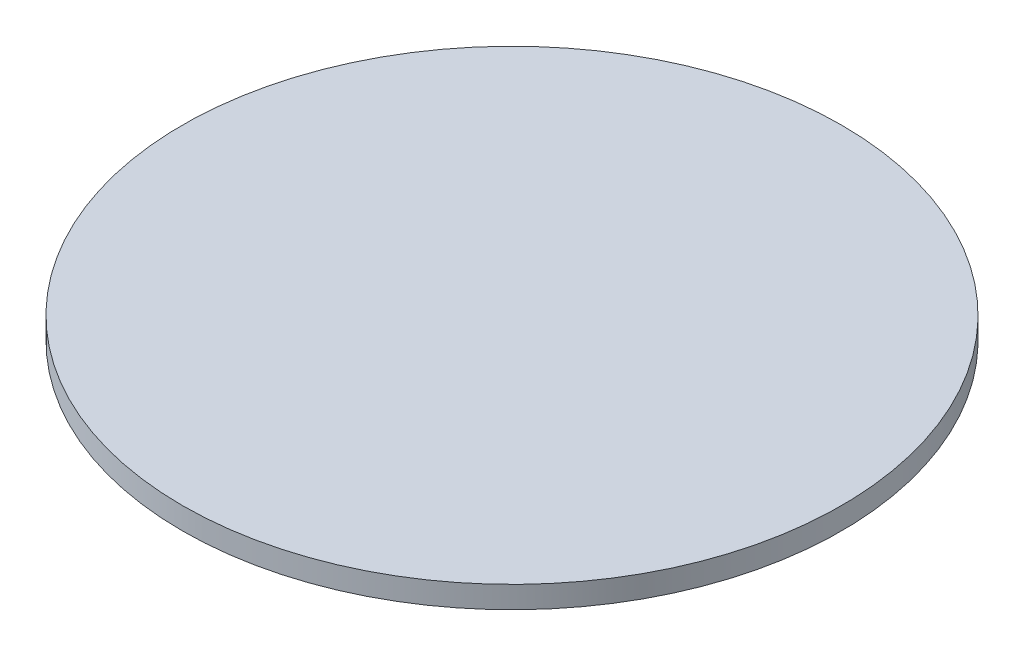
SolidWorks part; units mm, degrees
ref_plane "Ebene vorne" through (0, 0, 0) normal (0, 0, 1) x (1, 0, 0)
ref_plane "Ebene oben" through (0, 0, 0) normal (0, 1, 0) x (1, 0, 0)
ref_plane "Ebene rechts" through (0, 0, 0) normal (1, 0, 0) x (0, 0, -1)
sketch "Skizze1" plane through (0, 0, 0) normal (0, 1, 0) x (1, 0, 0)
  circle A0 centre (0, 0) radius 10
  dimension "D1" = 20
extrude "Aufsatz-Linear austragen1" add sketch "Skizze1" against normal blind 1
sketch "Skizze2" plane through (0, 0, 0) normal (0, 1, 0) x (1, 0, 0)
  circle A0 centre (0, 0) radius 30
  dimension "D1" = 60
extrude "Aufsatz-Linear austragen2" add sketch "Skizze2" along normal blind 2
sketch "Skizze3" plane through (0, -1, 0) normal (0, -1, 0) x (1, 0, 0)
  line L0 (-7.0711, 7.0711) -> (-9.1924, 9.1924)
  line L1 (7.0711, 7.0711) -> (9.1924, 9.1924)
  line L2 (7.0711, -7.0711) -> (9.1924, -9.1924)
  line L3 (-7.0711, -7.0711) -> (-9.1924, -9.1924)
  arc A0 (9.1924, 9.1924) -> (9.1924, -9.1924) centre (0, 0) cw
  arc A1 (-9.1924, 9.1924) -> (-9.1924, -9.1924) centre (0, 0) ccw
  circle A2 centre (0, 0) radius 10 construction
  circle A3 centre (0, 0) radius 10 construction
  arc A4 (-7.0711, 7.0711) -> (-7.0711, -7.0711) centre (0, 0) ccw
  arc A5 (7.0711, 7.0711) -> (7.0711, -7.0711) centre (0, 0) cw
extrude "Aufsatz-Linear austragen3" add sketch "Skizze3" along normal blind 1 separate body
sketch "Skizze4" plane through (0, -1, 0) normal (0, -1, 0) x (1, 0, 0)
  circle A0 centre (0, 0) radius 10
extrude "Aufsatz-Linear austragen4" add sketch "Skizze4" along normal blind 1
sketch "Skizze8" plane through (0, -1, 0) normal (0, 1, 0) x (1, 0, 0)
  line L0 (9.1924, -9.1924) -> (7.0711, -7.0711) construction
  line L1 (10.0765, -8.2136) -> (7.7376, -6.3348)
  line L2 (9.1924, -9.1924) -> (7.0711, -7.0711)
  line L3 (-7.0711, 7.0711) -> (-9.1924, 9.1924)
  line L4 (-10.0575, 8.2369) -> (-7.7328, 6.3407)
  arc A0 (7.0711, -7.0711) -> (7.7376, -6.3348) centre (0, 0) ccw
  arc A1 (9.1924, -9.1924) -> (10.0765, -8.2136) centre (0, 0) ccw
  arc A2 (-7.0711, 7.0711) -> (-7.7328, 6.3407) centre (0, 0) ccw
  arc A3 (-9.1924, 9.1924) -> (-10.0575, 8.2369) centre (0, 0) ccw
extrude "Aufsatz-Linear austragen15" add sketch "Skizze8" along normal blind 3
